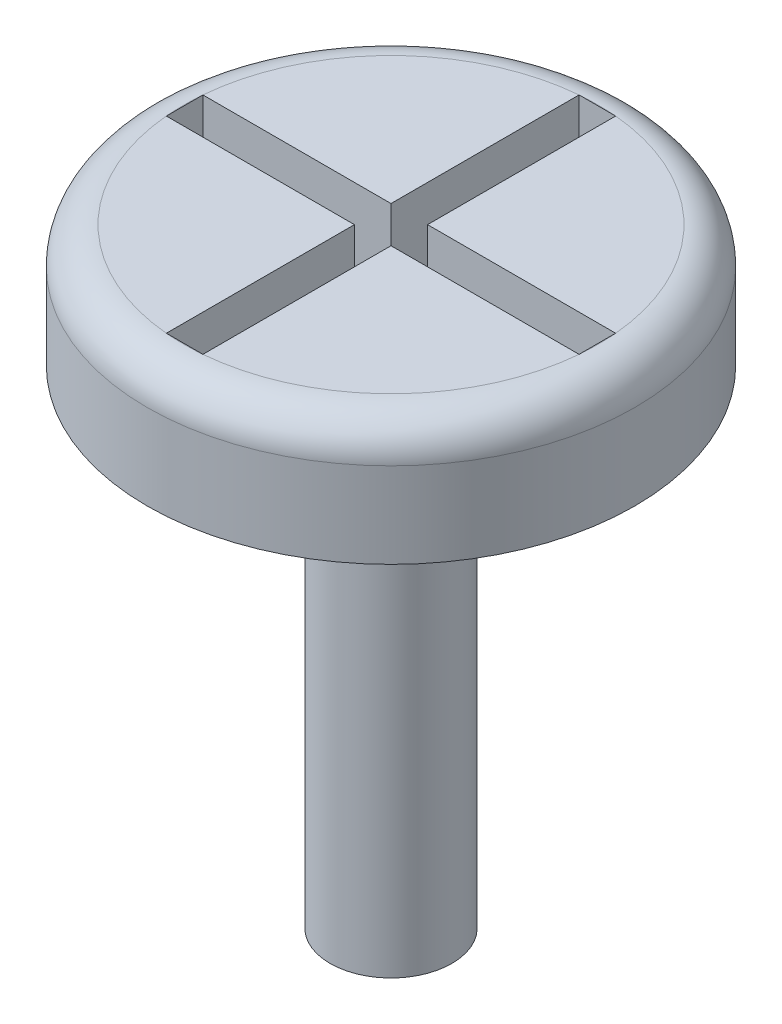
SolidWorks part; units mm, degrees
ref_plane "Front Plane" through (0, 0, 0) normal (0, 0, 1) x (1, 0, 0)
ref_plane "Top Plane" through (0, 0, 0) normal (0, 1, 0) x (1, 0, 0)
ref_plane "Right Plane" through (0, 0, 0) normal (1, 0, 0) x (0, 0, -1)
sketch "Sketch1" plane through (0, 0, 0) normal (0, 1, 0) x (1, 0, 0)
  circle A0 centre (0, 0) radius 0.5
extrude "Boss-Extrude1" add sketch "Sketch1" along normal blind 5
sketch "Sketch2" plane through (0, 5, 0) normal (0, 1, 0) x (1, 0, 0)
  circle A0 centre (0, 0) radius 2
extrude "Boss-Extrude2" add sketch "Sketch2" against normal blind 1
fillet "Fillet1" radius 0.3 1 edges at (0, 5, 2)
sketch "Sketch3" plane through (0, 5, 0) normal (0, 1, 0) x (1, 0, 0)
  line L0 (-0.15, 0.15) -> (-0.15, 1.6934)
  line L1 (-1.6934, -0.15) -> (-0.15, -0.15)
  line L2 (-1.6934, -0.15) -> (-1.6934, 0.15)
  line L3 (-1.6934, 0.15) -> (-0.15, 0.15)
  line L4 (1.6934, -0.15) -> (1.6934, 0.15)
  line L5 (0.15, -0.15) -> (1.6934, -0.15)
  line L6 (0.15, 0.15) -> (1.6934, 0.15)
  line L7 (-0.15, -1.6934) -> (0.15, -1.6934)
  line L8 (-0.15, -1.6934) -> (-0.15, -0.15)
  line L9 (-0.15, 1.6934) -> (0.15, 1.6934)
  line L10 (0.15, -1.6934) -> (0.15, -0.15)
  line L17 (0.15, 0.15) -> (0.15, 1.6934)
  circle A0 centre (0, 0) radius 1.7 construction
  point P0 (0, 0)
  point P8 (0, 0)
  dimension "D1" = 0.3
  dimension "D2" = 0.3
extrude "Cut-Extrude2" cut sketch "Sketch3" against normal blind 0.6
